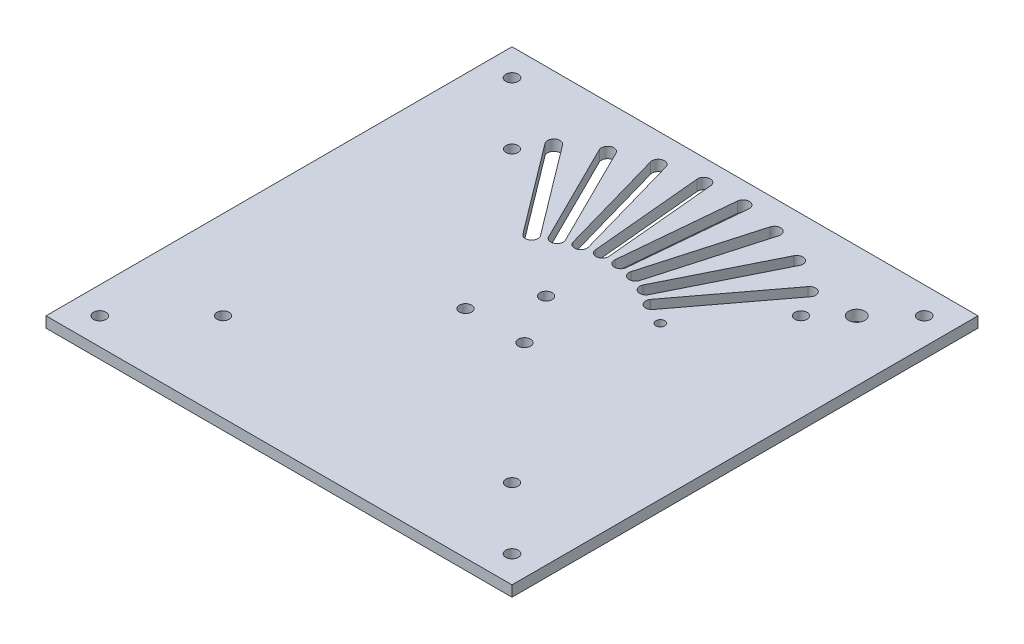
SolidWorks part; units mm, degrees
material "Acrylic (Medium-high impact)"
ref_plane "Front Plane" through (0, 0, 0) normal (0, 0, 1) x (1, 0, 0)
ref_plane "Top Plane" through (0, 0, 0) normal (0, 1, 0) x (1, 0, 0)
ref_plane "Right Plane" through (0, 0, 0) normal (1, 0, 0) x (0, 0, -1)
sketch "Sketch2" plane through (0, 0, 0) normal (0, 1, 0) x (1, 0, 0)
  line L1 (-65, -65) -> (65, -65)
  line L2 (-65, -65) -> (-65, 65)
  line L3 (-65, 65) -> (65, 65)
  line L4 (65, -65) -> (65, 65)
  line L5 (-65, -65) -> (65, 65) construction
  line L6 (-65, 65) -> (65, -65) construction
  point P0 (0, 0)
  dimension "D1" = 130
  dimension "D2" = 130
extrude "Boss-Extrude1" add sketch "Sketch2" along normal blind 3
sketch "Sketch4" plane through (0, 3, 0) normal (0, 1, 0) x (1, 0, 0)
  line L8 (57.5, -57.5) -> (57.5, 57.5)
  line L9 (57.5, 57.5) -> (-57.5, 57.5)
  line L10 (-57.5, 57.5) -> (-57.5, -57.5)
  line L11 (-57.5, -57.5) -> (57.5, -57.5)
  line L12 (57.5, -57.5) -> (57.5, 57.5) construction
  line L13 (57.5, 57.5) -> (-57.5, 57.5) construction
  line L14 (-57.5, 57.5) -> (-57.5, -57.5) construction
  line L15 (-57.5, -57.5) -> (57.5, -57.5) construction
  circle A0 centre (-57.5, 57.5) radius 1.75
  circle A1 centre (57.5, 57.5) radius 1.75
  circle A2 centre (57.5, -57.5) radius 1.75
  circle A3 centre (-57.5, -57.5) radius 1.75
  dimension "D2" = 3.5
  dimension "D1" = 7.5
extrude "Cornerpiece holes" cut sketch "Sketch4" against normal up to next
sketch "Sketch6" plane through (0, 3, 0) normal (0, 1, 0) x (1, 0, 0)
  line L6 (-40.3051, -40.3051) -> (40.3051, -40.3051) construction
  line L7 (-40.3051, -40.3051) -> (-40.3051, 40.3051) construction
  line L8 (-40.3051, 40.3051) -> (40.3051, 40.3051) construction
  line L9 (40.3051, -40.3051) -> (40.3051, 40.3051) construction
  line L10 (-40.3051, -40.3051) -> (40.3051, 40.3051) construction
  line L11 (-40.3051, 40.3051) -> (40.3051, -40.3051) construction
  circle A4 centre (-40.3051, 40.3051) radius 1.7
  circle A5 centre (40.3051, 40.3051) radius 1.7
  circle A6 centre (40.3051, -40.3051) radius 1.7
  circle A7 centre (-40.3051, -40.3051) radius 1.7
  point P0 (0, 0)
  dimension "D2" = 3.4
  dimension "D1" = 57
extrude "Cut-Extrude2" cut sketch "Sketch6" against normal up to next
sketch "Sketch8" plane through (0, 3, 0) normal (0, 1, 0) x (1, 0, 0)
  circle A4 centre (0, 9.5) radius 1.7
  circle A5 centre (8.2272, -4.75) radius 1.7
  circle A6 centre (-8.2272, -4.75) radius 1.7
  point P9 (0, 0)
  dimension "D1" = 9.5
  dimension "D3" = 3.4
  dimension "D2" = 3
extrude "Cut-Extrude3" cut sketch "Sketch8" against normal up to next
sketch "Sketch9" plane through (0, 3, 0) normal (0, 1, 0) x (1, 0, 0)
  line L0 (65, -65) -> (65, 65) construction
  line L1 (48.0833, 48.0833) -> (0, 0) construction
  line L2 (0, 0) -> (50000, 0) construction
  circle A0 centre (0, 0) radius 65 construction
  circle A1 centre (48.0833, 48.0833) radius 2.25
  dimension "D3" = 3
  dimension "D1" = 4.5
  dimension "D2" = 45
extrude "Primary wire hole" cut sketch "Sketch9" against normal up to next
sketch "Sketch10" plane through (0, 3, 0) normal (0, 1, 0) x (1, 0, 0)
  line L0 (0, 0) -> (22.5064, 18.8851) construction
  line L1 (0, 0) -> (50000, 0) construction
  circle A0 centre (0, 0) radius 24.13 construction
  circle A1 centre (22.5064, 18.8851) radius 1.25
  dimension "D1" = 48.26
  dimension "D3" = 2.5
  dimension "D2" = 40
  dimension "D4" = 4
extrude "Secondary wire hole" cut sketch "Sketch10" against normal up to next
sketch "Sketch11" plane through (0, 3, 0) normal (0, 1, 0) x (1, 0, 0)
  line L0 (-35.6575, 47.3192) -> (-16.7786, 22.266) construction
  line L1 (-34.2599, 48.3723) -> (-15.381, 23.3191)
  line L2 (-37.0552, 46.266) -> (-18.1762, 21.2128)
  line L3 (0, 0) -> (-16.7786, 22.266) construction
  line L4 (-27.9382, 52.2789) -> (-13.976, 24.1874)
  line L5 (-24.804, 53.8367) -> (-10.8418, 25.7452)
  line L6 (-26.3711, 53.0578) -> (-12.4089, 24.9663) construction
  line L7 (-17.8729, 56.5171) -> (-9.3013, 26.3409)
  line L8 (-14.5061, 57.4735) -> (-5.9345, 27.2972)
  line L9 (-16.1895, 56.9953) -> (-7.6179, 26.8191) construction
  line L10 (-7.2008, 58.8368) -> (-4.3109, 27.6002)
  line L11 (-3.7157, 59.1593) -> (-0.8258, 27.9227)
  line L12 (-5.4582, 58.9981) -> (-2.5684, 27.7614) construction
  line L13 (3.7157, 59.1593) -> (0.8258, 27.9227)
  line L14 (7.2008, 58.8368) -> (4.3109, 27.6002)
  line L15 (5.4582, 58.9981) -> (2.5684, 27.7614) construction
  line L18 (0, 0) -> (50000, 0) construction
  line L19 (14.5061, 57.4735) -> (5.9345, 27.2972)
  line L20 (17.8729, 56.5171) -> (9.3013, 26.3409)
  line L21 (16.1895, 56.9953) -> (7.6179, 26.8191) construction
  line L22 (24.804, 53.8367) -> (10.8418, 25.7452)
  line L23 (27.9382, 52.2789) -> (13.976, 24.1874)
  line L24 (26.3711, 53.0578) -> (12.4089, 24.9663) construction
  line L25 (34.2599, 48.3723) -> (15.381, 23.3191)
  line L26 (37.0552, 46.266) -> (18.1762, 21.2128)
  line L27 (35.6575, 47.3192) -> (16.7786, 22.266) construction
  line L28 (0, 0) -> (16.7786, 22.266) construction
  circle A0 centre (0, 0) radius 24.13 construction
  circle A1 centre (0, 0) radius 63 construction
  arc A2 (-34.2599, 48.3723) -> (-37.0552, 46.266) centre (-35.6575, 47.3192) ccw
  arc A3 (-18.1762, 21.2128) -> (-15.381, 23.3191) centre (-16.7786, 22.266) ccw
  arc A4 (-24.804, 53.8367) -> (-27.9382, 52.2789) centre (-26.3711, 53.0578) ccw
  arc A5 (-13.976, 24.1874) -> (-10.8418, 25.7452) centre (-12.4089, 24.9663) ccw
  arc A6 (-14.5061, 57.4735) -> (-17.8729, 56.5171) centre (-16.1895, 56.9953) ccw
  arc A7 (-9.3013, 26.3409) -> (-5.9345, 27.2972) centre (-7.6179, 26.8191) ccw
  arc A8 (-3.7157, 59.1593) -> (-7.2008, 58.8368) centre (-5.4582, 58.9981) ccw
  arc A9 (-4.3109, 27.6002) -> (-0.8258, 27.9227) centre (-2.5684, 27.7614) ccw
  arc A10 (7.2008, 58.8368) -> (3.7157, 59.1593) centre (5.4582, 58.9981) ccw
  arc A11 (0.8258, 27.9227) -> (4.3109, 27.6002) centre (2.5684, 27.7614) ccw
  arc A14 (17.8729, 56.5171) -> (14.5061, 57.4735) centre (16.1895, 56.9953) ccw
  arc A15 (5.9345, 27.2972) -> (9.3013, 26.3409) centre (7.6179, 26.8191) ccw
  arc A16 (27.9382, 52.2789) -> (24.804, 53.8367) centre (26.3711, 53.0578) ccw
  arc A17 (10.8418, 25.7452) -> (13.976, 24.1874) centre (12.4089, 24.9663) ccw
  arc A18 (37.0552, 46.266) -> (34.2599, 48.3723) centre (35.6575, 47.3192) ccw
  arc A19 (15.381, 23.3191) -> (18.1762, 21.2128) centre (16.7786, 22.266) ccw
  point P6 (-26.2181, 34.7926)
  point P17 (-19.39, 39.012)
  point P24 (-11.9037, 41.9072)
  point P31 (-4.0133, 43.3797)
  point P36 (0, 0)
  point P38 (4.0133, 43.3797)
  point P48 (11.9037, 41.9072)
  point P55 (19.39, 39.012)
  point P62 (26.2181, 34.7926)
  dimension "D1" = 48.26
  dimension "D2" = 126
  dimension "D3" = 2
  dimension "D4" = 2
  dimension "D5" = 3.5
  dimension "D7" = 53
  dimension "D8" = 53
  dimension "D6" = 8
extrude "Cut-Extrude6" cut sketch "Sketch11" against normal up to next
equation "\"D1@Sketch4\"=4.50+3"
equation "\"D1@Sketch10\"=1.9in"
equation "\"D1@Sketch11\"=1.9in"
equation "\"D2@Sketch11\"=130mm-2*2mm"
